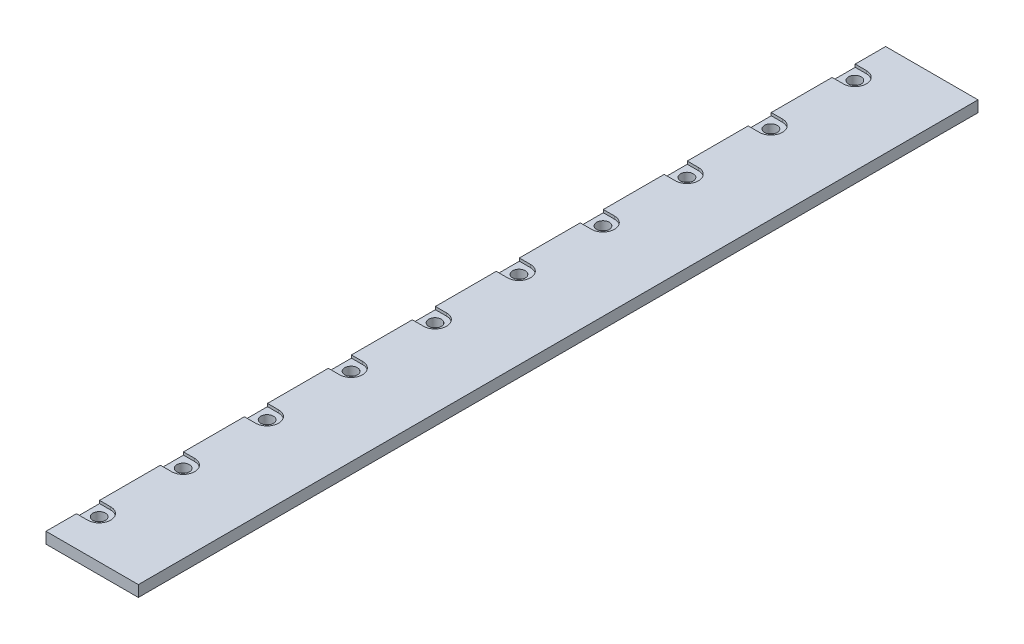
SolidWorks part; units mm, degrees
ref_plane "Front Plane" through (0, 0, 0) normal (0, 0, 1) x (1, 0, 0)
ref_plane "Top Plane" through (0, 0, 0) normal (0, 1, 0) x (1, 0, 0)
ref_plane "Right Plane" through (0, 0, 0) normal (1, 0, 0) x (0, 0, -1)
sketch "Sketch1" plane through (0, 0, 0) normal (0, 0, 1) x (1, 0, 0)
  line L1 (-16.5, -2) -> (16.5, -2)
  line L2 (-16.5, -2) -> (-16.5, 2)
  line L3 (-16.5, 2) -> (16.5, 2)
  line L4 (16.5, -2) -> (16.5, 2)
  line L5 (-16.5, -2) -> (16.5, 2) construction
  line L6 (-16.5, 2) -> (16.5, -2) construction
  point P0 (0, 0)
  dimension "D1" = 4
  dimension "D2" = 33
extrude "Boss-Extrude2" add sketch "Sketch1" along normal blind 300
sketch "Sketch2" plane through (0, 2, 0) normal (0, 1, 0) x (1, 0, 0)
  line L0 (-16.5, -300) -> (-16.5, 0) construction
  line L1 (16.5, 0) -> (-16.5, 0) construction
  line L7 (-12.5, -10.875) -> (-16.5, -10.875)
  line L8 (-16.5, -10.875) -> (-16.5, -19.125)
  line L9 (-16.5, -19.125) -> (-12.5, -19.125)
  arc A3 (-12.5, -19.125) -> (-12.5, -10.875) centre (-12.5, -15) ccw
  dimension "D1" = 8.25
  dimension "D3" = 15
  dimension "D2" = 4
extrude "Cut-Extrude2" cut sketch "Sketch2" against normal blind 1
sketch "Sketch5" plane through (0, 1, 0) normal (0, 1, 0) x (1, 0, 0)
  circle A0 centre (-12.5, -15) radius 2.25
  dimension "D1" = 4.5
extrude "Cut-Extrude3" cut sketch "Sketch5" against normal through all
pattern_linear "LPattern1" count 10 spacing 30 along (0, 0, 1) of "Cut-Extrude2", "Cut-Extrude3"
